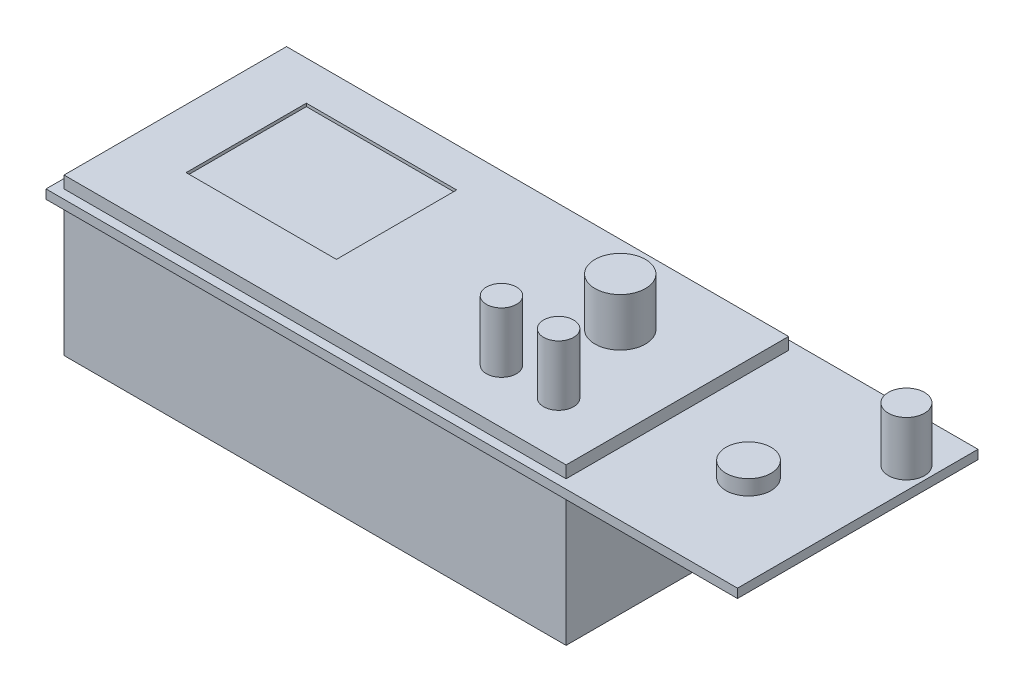
SolidWorks part; units mm, degrees
ref_plane "前视基准面" through (0, 0, 0) normal (0, 0, 1) x (1, 0, 0)
ref_plane "上视基准面" through (0, 0, 0) normal (0, 1, 0) x (1, 0, 0)
ref_plane "右视基准面" through (0, 0, 0) normal (1, 0, 0) x (0, 0, -1)
sketch "草图1" plane through (0, 0, 0) normal (0, 1, 0) x (1, 0, 0)
  line L1 (-79.6241, 38.2196) -> (150.3759, 38.2196)
  line L2 (-79.6241, 38.2196) -> (-79.6241, -41.7804)
  line L3 (-79.6241, -41.7804) -> (150.3759, -41.7804)
  line L4 (150.3759, 38.2196) -> (150.3759, -41.7804)
  dimension "D1" = 230
  dimension "D2" = 80
extrude "凸台-拉伸1" add sketch "草图1" along normal blind 3
sketch "草图2" plane through (0, 3, 0) normal (0, 1, 0) x (1, 0, 0)
  line L0 (-79.6241, 38.2196) -> (-79.6241, -41.7804) construction
  line L1 (-76.6241, 35.2196) -> (90.3759, 35.2196)
  line L2 (-76.6241, 35.2196) -> (-76.6241, -38.7804)
  line L3 (-76.6241, -38.7804) -> (90.3759, -38.7804)
  line L4 (90.3759, 35.2196) -> (90.3759, -38.7804)
  line L5 (150.3759, 38.2196) -> (-79.6241, 38.2196) construction
  line L6 (-79.6241, -41.7804) -> (150.3759, -41.7804) construction
  dimension "D1" = 3
  dimension "D2" = 3
  dimension "D3" = 3
  dimension "D4" = 167
  dimension "D5" = 74
extrude "凸台-拉伸2" add sketch "草图2" along normal blind 4
sketch "草图3" plane through (0, 7, 0) normal (0, 1, 0) x (1, 0, 0)
  line L0 (90.3759, 35.2196) -> (-76.6241, 35.2196) construction
  line L1 (-57.0241, 22.2196) -> (-7.0241, 22.2196)
  line L2 (-57.0241, 22.2196) -> (-57.0241, -17.7804)
  line L3 (-57.0241, -17.7804) -> (-7.0241, -17.7804)
  line L4 (-7.0241, 22.2196) -> (-7.0241, -17.7804)
  line L5 (-76.6241, 35.2196) -> (-76.6241, -38.7804) construction
  dimension "D1" = 50
  dimension "D2" = 40
  dimension "D3" = 13
  dimension "D4" = 19.6
extrude "切除-拉伸1" cut sketch "草图3" against normal blind 1
sketch "草图4" plane through (0, 7, 0) normal (0, 1, 0) x (1, 0, 0)
  line L0 (90.3759, -38.7804) -> (90.3759, 35.2196) construction
  line L2 (90.3759, 35.2196) -> (-76.6241, 35.2196) construction
  circle A0 centre (60.3759, 9.2196) radius 8.4
  point P6 (62.9387, 35.2196)
  dimension "D1" = 30
  dimension "D2" = 26
extrude "凸台-拉伸3" add sketch "草图4" along normal blind 16
sketch "草图5" plane through (0, 7, 0) normal (0, 1, 0) x (1, 0, 0)
  line L0 (60.3759, 9.2196) -> (60.3759, -33.6012) construction
  line L1 (50.8759, -20.7804) -> (69.8759, -20.7804) construction
  circle A0 centre (50.8759, -20.7804) radius 5
  circle A1 centre (69.8759, -20.7804) radius 5
  point P5 (60.3759, -20.7804)
  dimension "D1" = 30
  dimension "D2" = 19
extrude "凸台-拉伸4" add sketch "草图5" along normal blind 20
sketch "草图6" plane through (0, 3, 0) normal (0, 1, 0) x (1, 0, 0)
  line L0 (150.3759, 38.2196) -> (-79.6241, 38.2196) construction
  line L3 (150.3759, -41.7804) -> (150.3759, 38.2196) construction
  circle A0 centre (143.0759, 21.7196) radius 6
  point P6 (150.3759, 22.004)
  point P7 (150.3759, 19.6256)
  point P8 (0, 0)
  dimension "D1" = 16.5
  dimension "D2" = 7.3
extrude "凸台-拉伸5" add sketch "草图6" along normal blind 18
sketch "草图7" plane through (0, 3, 0) normal (0, 1, 0) x (1, 0, 0)
  line L0 (90.3759, -38.7804) -> (90.3759, 35.2196) construction
  line L1 (90.3759, -8.1084) -> (150.3759, -8.1084) construction
  line L2 (150.3759, -41.7804) -> (150.3759, 38.2196) construction
  circle A0 centre (120.3759, -8.1084) radius 7.5
  point P8 (120.3759, -8.1084)
  point P9 (0, 0)
extrude "凸台-拉伸6" add sketch "草图7" along normal blind 5
sketch "草图8" plane through (0, 0, 0) normal (0, -1, 0) x (1, 0, 0)
  line L0 (-79.6241, -38.2196) -> (-79.6241, 41.7804) construction
  line L1 (-76.6241, 38.7804) -> (90.3759, 38.7804)
  line L2 (-76.6241, 38.7804) -> (-76.6241, -35.2196)
  line L3 (-76.6241, -35.2196) -> (90.3759, -35.2196)
  line L4 (90.3759, 38.7804) -> (90.3759, -35.2196)
  line L5 (-79.6241, 41.7804) -> (150.3759, 41.7804) construction
  line L6 (150.3759, -38.2196) -> (-79.6241, -38.2196) construction
  dimension "D1" = 3
  dimension "D2" = 3
  dimension "D3" = 3
  dimension "D4" = 167
extrude "凸台-拉伸7" add sketch "草图8" along normal blind 45
